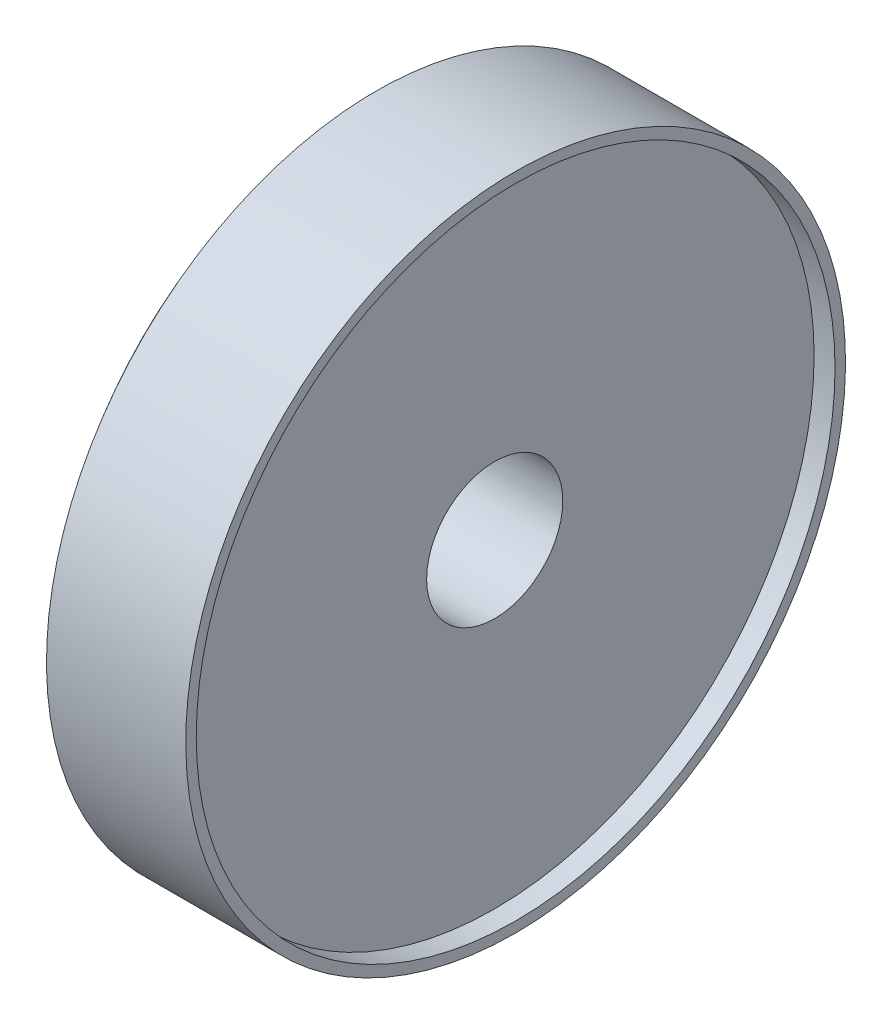
SolidWorks part; units mm, degrees
ref_plane "Front" through (0, 0, 0) normal (0, 0, 1) x (1, 0, 0)
ref_plane "Top" through (0, 0, 0) normal (0, 1, 0) x (1, 0, 0)
ref_plane "Right" through (0, 0, 0) normal (1, 0, 0) x (0, 0, -1)
sketch "Sketch1" plane through (0, 0, 0) normal (0, 0, 1) x (1, 0, 0)
  line L0 (-7.9, 0) -> (7.9, 0)
  line L1 (7.9, 0) -> (7.9, 31.5)
  line L2 (7.9, 31.5) -> (-5.4, 31.5)
  line L4 (-7.9, 0) -> (-7.9, 28)
  line L5 (-7.9, 28) -> (-5.4, 31.5)
  point P4 (0, 0)
  dimension "D1" = 28
  dimension "D2" = 31.5
  dimension "D3" = 2.5
  dimension "D4" = 15.8
revolve "Revolve1" add sketch "Sketch1" angle 360 about L0
sketch "Sketch2" plane through (7.9, 0, 0) normal (1, 0, 0) x (0, 0, -1)
  circle A0 centre (0, 0) radius 30.5
  circle A1 centre (0, 0) radius 31.5 construction
  dimension "D1" = 1
extrude "Cut-Extrude1" cut sketch "Sketch2" against normal blind 2
sketch "Sketch3" plane through (-7.9, 0, 0) normal (-1, 0, 0) x (0, 0, 1)
  line L0 (0, 0) -> (0, 22) construction
  line L1 (-15.5563, -15.5563) -> (15.5563, 15.5563) construction
  line L2 (15.5563, -15.5563) -> (-15.5563, 15.5563) construction
  circle A0 centre (0, 0) radius 22 construction
  point P7 (0, 0)
  point P10 (0, 0)
  dimension "D1" = 44
  dimension "D2" = 45
hole_wizard "M3x0.5 Tapped Hole1" positions "Sketch4" profile "Sketch5" tap size "M3x0.5" standard "ANSI Metric"
sketch "Sketch4" plane through (-7.9, 0, 0) normal (-1, 0, 0) x (0, 0, 1)
  point P0 (-15.5563, 15.5563)
  point P3 (15.5563, 15.5563)
  point P6 (15.5563, -15.5563)
  point P9 (-15.5563, -15.5563)
sketch "Sketch5" plane through (-7.9, 15.5563, -15.5563) normal (0, 1, 0) x (0, 0, 1)
  line L0 (0, 0) -> (0, 8.2511)
  line L1 (0, 8.2511) -> (1.25, 7.5)
  line L2 (1.25, 7.5) -> (1.25, 0)
  line L5 (1.25, 0) -> (0, 0)
  line L10 (0, 8.2511) -> (-1.25, 7.5) construction
  line L11 (0, -6.35) -> (0, 107.95) construction
  dimension "Tap Drill Dia." = 2.5
  dimension "Tap Drill Depth" = 7.5
  dimension "Drill Angle" = 118
cosmetic thread "Hole Thread1" parameters "D1"=6, "D2"=3
cosmetic thread "Hole Thread2" parameters "D1"=6, "D2"=3
cosmetic thread "Hole Thread3" parameters "D1"=6, "D2"=3
cosmetic thread "Hole Thread4" parameters "D1"=6, "D2"=3
sketch "Sketch6" plane through (-7.9, 0, 0) normal (-1, 0, 0) x (0, 0, 1)
  line L0 (10.6066, -10.6066) -> (-10.6066, 10.6066) construction
  line L1 (-10.6066, -10.6066) -> (10.6066, 10.6066) construction
  line L2 (0, 0) -> (0, 15) construction
  circle A0 centre (0, 0) radius 15 construction
  circle A1 centre (0, 0) radius 12.5 construction
  point P5 (0, 0)
  point P8 (0, 0)
  point P11 (0, 12.5)
  point P12 (-12.5, 0)
  point P13 (0, -12.5)
  point P14 (12.5, 0)
  dimension "D1" = 30
  dimension "D4" = 25
  dimension "D2" = 90
  dimension "D3" = 45
hole_wizard "M3x0.5 Tapped Hole2" positions "Sketch7" profile "Sketch8" tap size "M3x0.5" standard "ANSI Metric"
sketch "Sketch7" plane through (-7.9, 0, 0) normal (-1, 0, 0) x (0, 0, 1)
  point P0 (-10.6066, 10.6066)
  point P3 (-10.6066, -10.6066)
  point P6 (10.6066, -10.6066)
  point P9 (10.6066, 10.6066)
sketch "Sketch8" plane through (-7.9, 10.6066, -10.6066) normal (0, 1, 0) x (0, 0, 1)
  line L0 (0, 0) -> (0, 8.2511)
  line L1 (0, 8.2511) -> (1.25, 7.5)
  line L2 (1.25, 7.5) -> (1.25, 0.275)
  line L3 (1.25, 0.275) -> (1.525, 0)
  line L5 (1.525, 0) -> (0, 0)
  line L6 (-1.25, 0.275) -> (-1.525, 0) construction
  line L10 (0, 8.2511) -> (-1.25, 7.5) construction
  line L11 (0, -6.35) -> (0, 107.95) construction
  dimension "Tap Drill Dia." = 2.5
  dimension "Tap Drill Depth" = 7.5
  dimension "Near C'Sink Dia." = 3.05
  dimension "Near C'Sink Angle" = 90
  dimension "Drill Angle" = 118
cosmetic thread "Hole Thread5" parameters "D1"=6, "D2"=3
cosmetic thread "Hole Thread6" parameters "D1"=6, "D2"=3
cosmetic thread "Hole Thread7" parameters "D1"=6, "D2"=3
cosmetic thread "Hole Thread8" parameters "D1"=6, "D2"=3
hole_wizard "M3x0.5 Tapped Hole3" positions "Sketch9" profile "Sketch10" tap size "M3x0.5" standard "ANSI Metric"
sketch "Sketch9" plane through (-7.9, 0, 0) normal (-1, 0, 0) x (0, 0, 1)
  point P0 (0, 12.5)
  point P3 (-12.5, 0)
  point P6 (0, -12.5)
  point P9 (12.5, 0)
sketch "Sketch10" plane through (-7.9, 12.5, 0) normal (0, 1, 0) x (0, 0, 1)
  line L0 (0, 0) -> (0, 8.2511)
  line L1 (0, 8.2511) -> (1.25, 7.5)
  line L2 (1.25, 7.5) -> (1.25, 0.275)
  line L3 (1.25, 0.275) -> (1.525, 0)
  line L5 (1.525, 0) -> (0, 0)
  line L6 (-1.25, 0.275) -> (-1.525, 0) construction
  line L10 (0, 8.2511) -> (-1.25, 7.5) construction
  line L11 (0, -6.35) -> (0, 107.95) construction
  dimension "Tap Drill Dia." = 2.5
  dimension "Tap Drill Depth" = 7.5
  dimension "Near C'Sink Dia." = 3.05
  dimension "Near C'Sink Angle" = 90
  dimension "Drill Angle" = 118
cosmetic thread "Hole Thread9" parameters "D1"=6, "D2"=3
cosmetic thread "Hole Thread10" parameters "D1"=6, "D2"=3
cosmetic thread "Hole Thread11" parameters "D1"=6, "D2"=3
cosmetic thread "Hole Thread12" parameters "D1"=6, "D2"=3
sketch "Sketch11" plane through (-7.9, 0, 0) normal (-1, 0, 0) x (0, 0, 1)
  circle A0 centre (0, 0) radius 6.5
  dimension "D1" = 13
extrude "Cut-Extrude2" cut sketch "Sketch11" against normal up to surface (13.8 mm away) up to face at (5.9, 30.5, 0)
